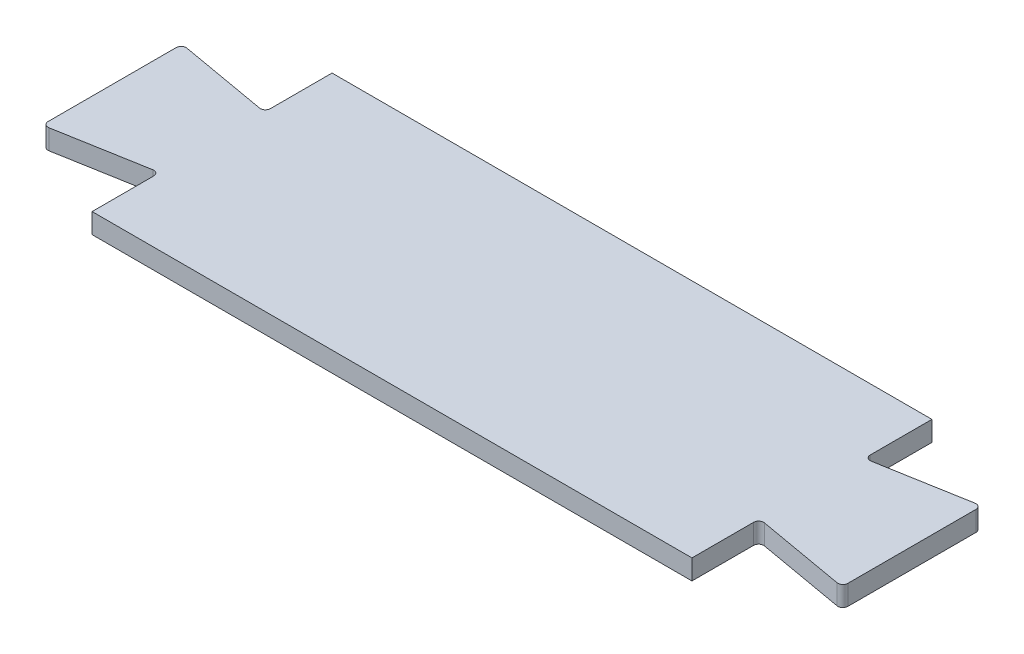
SolidWorks part; units mm, degrees
ref_plane "Front Plane" through (0, 0, 0) normal (0, 0, 1) x (1, 0, 0)
ref_plane "Top Plane" through (0, 0, 0) normal (0, 1, 0) x (1, 0, 0)
ref_plane "Right Plane" through (0, 0, 0) normal (1, 0, 0) x (0, 0, -1)
sketch "Sketch1" plane through (0, 0, 0) normal (0, 1, 0) x (1, 0, 0)
  line L0 (-15, 2.6184) -> (-20, 3.5)
  line L1 (-15, -6) -> (15, -6)
  line L2 (-15, -6) -> (-15, -2.6184)
  line L3 (-15, 6) -> (15, 6)
  line L4 (15, -6) -> (15, -2.6184)
  line L5 (-15, -6) -> (15, 6) construction
  line L6 (-15, 6) -> (15, -6) construction
  line L7 (-20, 3.5) -> (-20, -3.5)
  line L8 (-10, 0) -> (-18.3718, 0) construction
  line L9 (-15, -2.6184) -> (-20, -3.5)
  line L10 (-15, 2.6184) -> (-15, 6)
  line L11 (0, 0) -> (0, 6) construction
  line L12 (15, -2.6184) -> (20, -3.5)
  line L13 (20, 3.5) -> (20, -3.5)
  line L14 (15, 2.6184) -> (20, 3.5)
  line L15 (15, 2.6184) -> (15, 6)
  line L16 (-15, 6) -> (-25.4194, 6) construction
  point P0 (0, 0)
  point P13 (-20, 0)
  dimension "D1" = 12
  dimension "D2" = 30
  dimension "D3" = 3.5
  dimension "D4" = 80
  dimension "D5" = 5
extrude "Boss-Extrude1" add sketch "Sketch1" along normal blind 1
fillet "Fillet1" radius 0.25 8 edges at (-15, 0.5, 2.6184) (-20, 0.5, 3.5) (-20, 0.5, -3.5) (-15, 0.5, -2.6184) (15, 0.5, -2.6184) (20, 0.5, -3.5) (20, 0.5, 3.5) (15, 0.5, 2.6184)
